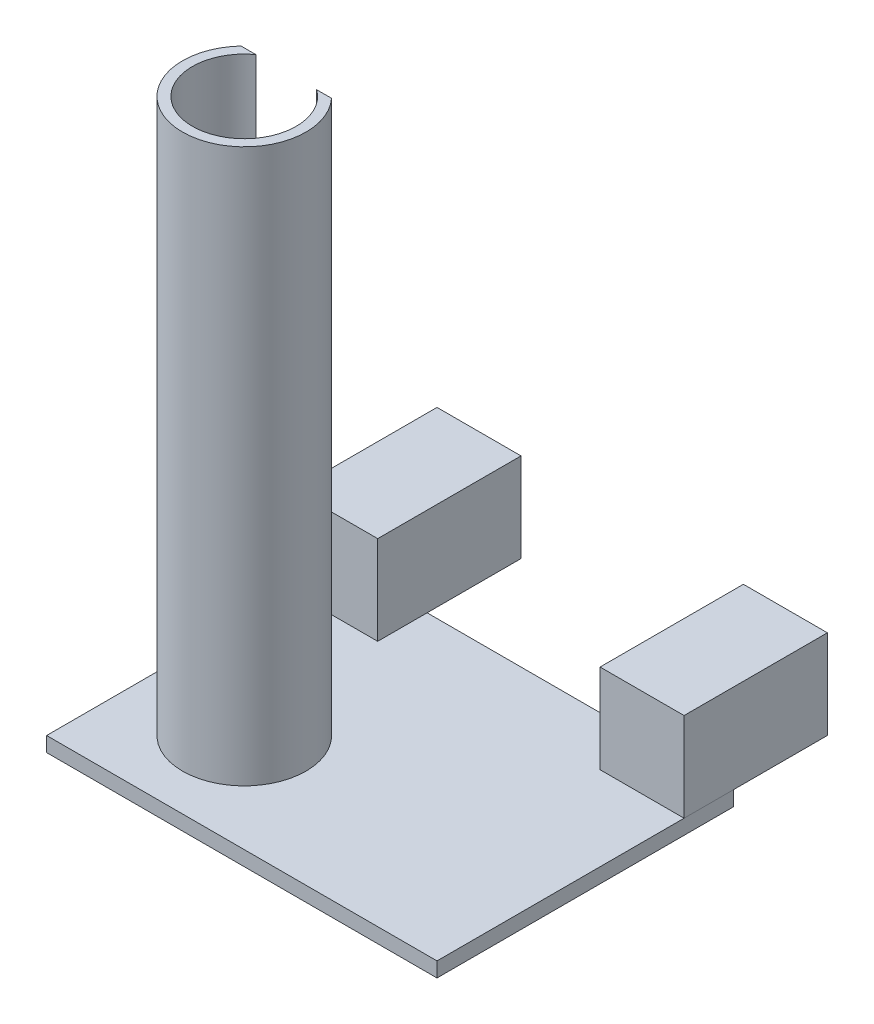
SolidWorks part; units mm, degrees
ref_plane "Front Plane" through (0, 0, 0) normal (0, 0, 1) x (1, 0, 0)
ref_plane "Top Plane" through (0, 0, 0) normal (0, 1, 0) x (1, 0, 0)
ref_plane "Right Plane" through (0, 0, 0) normal (1, 0, 0) x (0, 0, -1)
sketch "Sketch1" plane through (0, 0, 0) normal (0, 1, 0) x (1, 0, 0)
  line L1 (-39.5, -30) -> (39.5, -30)
  line L2 (-39.5, -30) -> (-39.5, 30)
  line L3 (-39.5, 30) -> (39.5, 30)
  line L4 (39.5, -30) -> (39.5, 30)
  line L5 (-39.5, -30) -> (39.5, 30) construction
  line L6 (-39.5, 30) -> (39.5, -30) construction
  point P0 (0, 0)
  dimension "D1" = 79
  dimension "D2" = 60
extrude "Boss-Extrude1" add sketch "Sketch1" along normal blind 3
sketch "Sketch2" plane through (0, 3, 0) normal (0, 1, 0) x (1, 0, 0)
  line L1 (-39.5, 20) -> (-22.5, 20)
  line L2 (-39.5, 20) -> (-39.5, 49)
  line L3 (-39.5, 49) -> (-22.5, 49)
  line L4 (-22.5, 20) -> (-22.5, 49)
  point P5 (0, 0)
  dimension "D1" = 29
  dimension "D2" = 17
extrude "Boss-Extrude2" add sketch "Sketch2" along normal blind 18 separate body
sketch "Sketch3" plane through (0, 3, 0) normal (0, -1, 0) x (1, 0, 0)
  line L0 (-22.5, -20) -> (-22.5, -49) construction
  line L1 (-38, -32.5) -> (-24, -32.5)
  line L2 (-38, -32.5) -> (-38, -46.5)
  line L3 (-38, -46.5) -> (-24, -46.5)
  line L4 (-24, -32.5) -> (-24, -46.5)
  line L5 (-22.5, -49) -> (-39.5, -49) construction
  dimension "D1" = 14
  dimension "D2" = 14
  dimension "D3" = 1.5
  dimension "D4" = 2.5
extrude "Cut-Extrude1" cut sketch "Sketch3" against normal blind 16
mirror "Mirror1" about plane through (0, 0, 0) normal (1, 0, 0) of bodies 103
sketch "Sketch5" plane through (0, 3, 0) normal (0, 1, 0) x (1, 0, 0)
  line L0 (-39.5, -30) -> (0.5, -30) construction
  line L1 (-39.5, -30) -> (39.5, -30) construction
  line L2 (0.5, -30) -> (0.5, 10) construction
  line L3 (0.5, 10) -> (-39.5, 10) construction
  line L4 (-39.5, 30) -> (-39.5, -30) construction
  line L5 (-39.5, 10) -> (-39.5, -30) construction
  line L6 (-39.5, -30) -> (-39.3198, -29.9488) construction
  line L7 (-19.5, 10) -> (-19.5, -30) construction
  line L8 (-39.5, -10) -> (1.2009, -10) construction
  circle A0 centre (-19.5, -10) radius 12.5
  dimension "D5" = 25
  dimension "D1" = 40
  dimension "D2" = 40
  dimension "D3" = 20
  dimension "D4" = 20
extrude "Boss-Extrude3" add sketch "Sketch5" along normal blind 112
sketch "Sketch7" plane through (0, 3, 0) normal (0, 1, 0) x (1, 0, 0)
  line L0 (-39.5, -30) -> (0.5, -30) construction
  line L1 (-39.5, -30) -> (39.5, -30) construction
  line L2 (0.5, -30) -> (0.5, 10) construction
  line L3 (0.5, 10) -> (-39.5, 10) construction
  line L4 (-39.5, 30) -> (-39.5, -30) construction
  line L5 (-39.5, 10) -> (-39.5, -30) construction
  line L6 (-39.5, 10) -> (0.5, 10)
  line L9 (-39.5, 10) -> (-39.5, -1.5)
  line L10 (-39.5, -1.5) -> (0.5, -1.5)
  line L11 (0.5, 10) -> (0.5, -1.5)
  dimension "D1" = 40
  dimension "D2" = 40
  dimension "D3" = 11.5
extrude "Cut-Extrude2" cut sketch "Sketch7" along normal blind 112
sketch "Sketch8" plane through (0, 3, 0) normal (0, 1, 0) x (1, 0, 0)
  line L0 (-39.5, -30) -> (0.5, -30) construction
  line L1 (-39.5, -30) -> (39.5, -30) construction
  line L2 (0.5, -30) -> (0.5, 10) construction
  line L3 (0.5, 10) -> (-39.5, 10) construction
  line L4 (-39.5, 30) -> (-39.5, -30) construction
  line L5 (-39.5, 10) -> (-39.5, -30) construction
  line L6 (-19.5, 10) -> (-19.5, -30) construction
  line L7 (-39.5, -10) -> (0.5, -10) construction
  circle A0 centre (-19.5, -10) radius 10.5
  dimension "D5" = 21
  dimension "D1" = 40
  dimension "D2" = 40
  dimension "D3" = 20
  dimension "D4" = 20
extrude "Cut-Extrude3" cut sketch "Sketch8" along normal blind 112 contours A0
